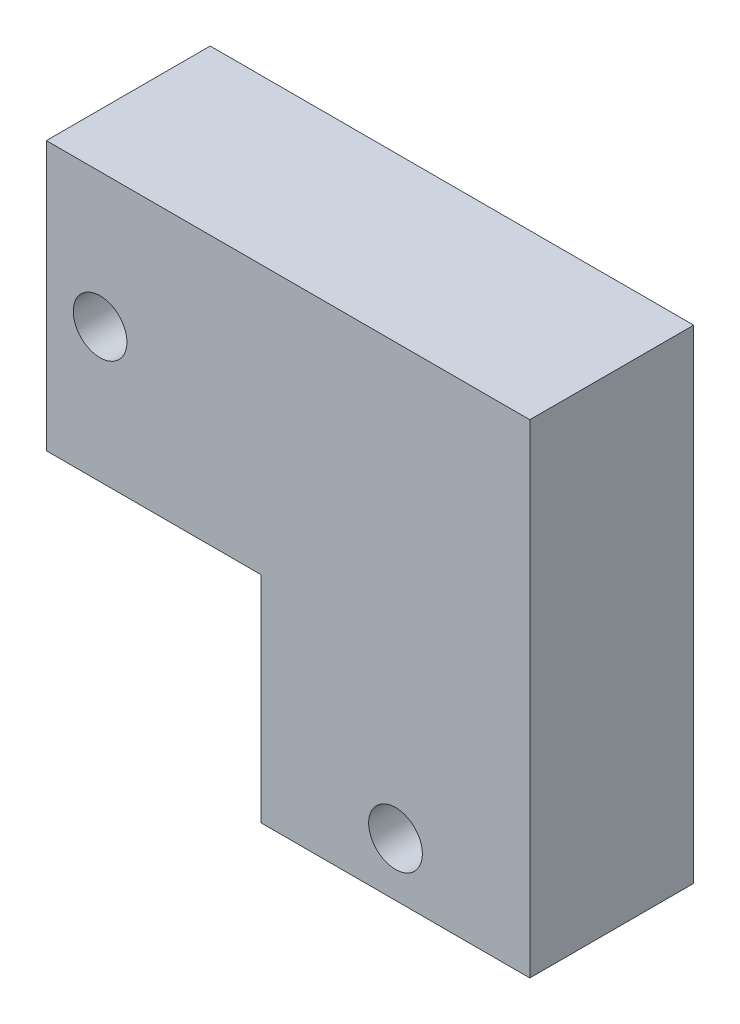
SolidWorks part; units mm, degrees
ref_plane "Front Plane" through (0, 0, 0) normal (0, 0, 1) x (1, 0, 0)
ref_plane "Top Plane" through (0, 0, 0) normal (0, 1, 0) x (1, 0, 0)
ref_plane "Right Plane" through (0, 0, 0) normal (1, 0, 0) x (0, 0, -1)
sketch "Sketch1" plane through (0, 0, 0) normal (0, 1, 0) x (1, 0, 0)
  line L1 (-12.5, -12.5) -> (12.5, -12.5)
  line L2 (-12.5, -12.5) -> (-12.5, 12.5)
  line L3 (-12.5, 12.5) -> (12.5, 12.5)
  line L4 (12.5, -12.5) -> (12.5, 12.5)
  line L5 (-12.5, -12.5) -> (12.5, 12.5) construction
  line L6 (-12.5, 12.5) -> (12.5, -12.5) construction
  point P0 (0, 0)
  dimension "D1" = 25
  dimension "D2" = 25
extrude "Boss-Extrude1" add sketch "Sketch1" along normal mid plane 45 contours L3 L4 L1 L2
sketch "Sketch3" plane through (0, -22.5, 0) normal (0, -1, 0) x (1, 0, 0)
  line L0 (0, 12.5) -> (0, 10.25) construction
  line L1 (-12.5, 12.5) -> (12.5, 12.5) construction
  line L2 (0, -12.5) -> (0, -9.9959) construction
  line L3 (-12.5, -12.5) -> (12.5, -12.5) construction
  line L4 (-12.5, 0) -> (-12.4984, 0) construction
  line L5 (-12.5, 12.5) -> (-12.5, -12.5) construction
  line L6 (12.5, 0) -> (12.4984, 0) construction
  line L7 (12.5, 12.5) -> (12.5, -12.5) construction
  line L8 (0, 10.25) -> (-2.75, 10.25)
  line L9 (-10.25, -10.25) -> (10.25, -10.25)
  line L10 (-10.25, -10.25) -> (-10.25, 10.25)
  line L11 (-10.25, 10.25) -> (10.25, 10.25)
  line L12 (10.25, -10.25) -> (10.25, 10.25)
  line L13 (-10.25, -10.25) -> (10.25, 10.25) construction
  line L14 (-10.25, 10.25) -> (10.25, -10.25) construction
  line L15 (-2.75, 10.25) -> (-2.75, 4.75)
  line L16 (-2.75, 4.75) -> (2.75, 4.75)
  line L17 (2.75, 4.75) -> (2.75, 10.25)
  line L18 (0, 10.25) -> (0, -9.9959) construction
  line L19 (-12.4984, 0) -> (12.4984, 0) construction
  line L20 (-2.75, -10.25) -> (-2.75, -4.75)
  line L21 (-2.75, -4.75) -> (2.75, -4.75)
  line L22 (2.75, -4.75) -> (2.75, -10.25)
  line L23 (-12.4984, 0) -> (-10.25, 2.75)
  line L24 (-10.25, 2.75) -> (-4.75, 2.75)
  line L25 (-4.75, 2.75) -> (-4.75, -2.75)
  line L26 (-4.75, -2.75) -> (-10.25, -2.75)
  line L27 (12.4984, 0) -> (10.25, 2.75)
  line L28 (10.25, 2.75) -> (4.75, 2.75)
  line L29 (4.75, 2.75) -> (4.75, -2.75)
  line L30 (4.75, -2.75) -> (10.25, -2.75)
  point P17 (0, 0)
  dimension "D1" = 5.5
  dimension "D2" = 5.5
  dimension "D3" = 5.5
  dimension "D4" = 5.5
  dimension "D5" = 2.75
  dimension "D6" = 5.5
  dimension "D7" = 2.75
  dimension "D8" = 5.5
  dimension "D9" = 2.75
  dimension "D10" = 5.5
  dimension "D11" = 2.25
  dimension "D12" = 2.25
  dimension "D13" = 5.5
sketch "Sketch4" plane through (-12.5, 0, 0) normal (-1, 0, 0) x (0, 0, 1)
  line L0 (0, 22.5) -> (0, 0) construction
  line L1 (12.5, 22.5) -> (-12.5, 22.5) construction
  line L3 (-12.5, 22.5) -> (-12.5, -22.5) construction
  line L6 (12.5, 22.5) -> (12.5, -22.5) construction
  line L8 (-12.5, 0) -> (12.5, 0) construction
  line L10 (-12.5, 22.5) -> (12.5, 22.5)
  line L11 (-12.5, 22.5) -> (-12.5, -2.5)
  line L12 (-12.5, -2.5) -> (12.5, -2.5)
  line L13 (12.5, 22.5) -> (12.5, -2.5)
  dimension "D1" = 25
extrude "Boss-Extrude2" add sketch "Sketch4" along normal blind 20
sketch "Sketch5" plane through (-32.5, 0, 0) normal (-1, 0, 0) x (0, 0, 1)
  line L0 (-12.5, 22.5) -> (12.5, -2.5) construction
  line L1 (0, 20.5) -> (0, -0.5) construction
  line L2 (-10.5, -0.5) -> (10.5, -0.5)
  line L3 (-10.5, -0.5) -> (-10.5, 20.5)
  line L4 (-10.5, 20.5) -> (10.5, 20.5)
  line L5 (10.5, -0.5) -> (10.5, 20.5)
  line L6 (-10.5, -0.5) -> (10.5, 20.5) construction
  line L7 (-10.5, 20.5) -> (10.5, -0.5) construction
  line L8 (-10.5, 10) -> (10.5, 10) construction
  line L9 (0, 20.5) -> (-2.75, 20.5)
  line L10 (-2.75, 20.5) -> (-2.75, 15)
  line L11 (-2.75, 15) -> (2.75, 15)
  line L12 (2.75, 15) -> (2.75, 20.5)
  line L13 (-10.5, 10) -> (-10.5, 7.25)
  line L14 (-10.5, 7.25) -> (-5, 7.25)
  line L15 (-5, 7.25) -> (-5, 12.75)
  line L16 (-5, 12.75) -> (-10.5, 12.75)
  line L17 (0, -0.5) -> (-2.75, -0.5)
  line L18 (-2.75, -0.5) -> (-2.75, 5)
  line L19 (-2.75, 5) -> (2.75, 5)
  line L20 (2.75, 5) -> (2.75, -0.5)
  line L21 (10.5, 7.25) -> (5, 7.25)
  line L22 (5, 7.25) -> (5, 12.75)
  line L23 (5, 12.75) -> (10.5, 12.75)
  point P4 (0, 10)
  dimension "D1" = 21
  dimension "D2" = 5.5
  dimension "D3" = 5.5
  dimension "D4" = 5.5
  dimension "D5" = 5.5
  dimension "D6" = 5.5
  dimension "D7" = 5.5
  dimension "D8" = 5.5
  dimension "D9" = 5.5
  dimension "D10" = 2.75
  dimension "D11" = 2.75
  dimension "D12" = 2.75
extrude "Cut-Extrude2" cut sketch "Sketch3" against normal blind 42.5 contours L30 L29 L28 L12 L11 L17 L16 L15 L10 L24 L25 L26 L9 L20 L21 L22
extrude "Cut-Extrude3" cut sketch "Sketch5" against normal blind 21 contours L22 L23 L5 L4 L12 L11 L10 L3 L16 L15 L14 L2 L18 L19 L20 L21
sketch "Sketch6" plane through (0, 0, -12.5) normal (0, 0, -1) x (-1, 0, 0)
  line L0 (0, -22.5) -> (0, -12.5) construction
  line L1 (12.5, -22.5) -> (-12.5, -22.5) construction
  line L2 (22.5, 10) -> (32.5, 10) construction
  line L3 (32.5, 22.5) -> (32.5, -2.5) construction
  circle A0 centre (0, -12.5) radius 2.25
  circle A1 centre (22.5, 10) radius 2.25
  dimension "D1" = 4.5
  dimension "D2" = 4.5
  dimension "D3" = 10
  dimension "D4" = 10
extrude "Cut-Extrude4" cut sketch "Sketch6" against normal blind 10
sketch "Sketch8" plane through (0, 22.5, 0) normal (0, 1, 0) x (1, 0, 0)
  line L0 (12.5, -12.5) -> (12.5, 12.5) construction
  line L1 (-32.5, 12.5) -> (12.5, 12.5)
  line L2 (-32.5, 12.5) -> (-32.5, 2.75)
  line L3 (-32.5, 2.75) -> (12.5, 2.75)
  line L4 (12.5, 12.5) -> (12.5, 2.75)
extrude "Cut-Extrude5" cut sketch "Sketch8" against normal blind 50
sketch "Sketch10" plane through (0, 0, 12.5) normal (0, 0, 1) x (1, 0, 0)
  line L0 (-32.5, 10) -> (12.5, 10) construction
  line L1 (-32.5, -2.5) -> (-32.5, 22.5) construction
  line L2 (12.5, 15) -> (12.5, -22.5) construction
  line L3 (0, -22.5) -> (0, 10) construction
  line L4 (-12.5, -22.5) -> (12.5, -22.5) construction
  circle A0 centre (-27.5, 10) radius 2.5
  circle A1 centre (0, -17.5) radius 2.5
  dimension "D1" = 5
  dimension "D2" = 5
  dimension "D3" = 5
  dimension "D4" = 5
extrude "Cut-Extrude7" cut sketch "Sketch10" against normal blind 10
sketch "Sketch11" plane through (0, 0, 4.75) normal (0, 0, -1) x (-1, 0, 0)
  line L1 (2.2226, -13.5502) -> (-2.3093, -13.6003)
  line L2 (-2.3093, -13.6003) -> (-4.5319, -17.55)
  line L3 (-4.5319, -17.55) -> (-2.2226, -21.4498)
  line L4 (-2.2226, -21.4498) -> (2.3093, -21.3997)
  line L5 (2.3093, -21.3997) -> (4.5319, -17.45)
  line L6 (4.5319, -17.45) -> (2.2226, -13.5502)
  line L7 (31.439, 12.2417) -> (27.5281, 14.5321)
  line L8 (27.5281, 14.5321) -> (23.5891, 12.2904)
  line L9 (23.5891, 12.2904) -> (23.561, 7.7583)
  line L10 (23.561, 7.7583) -> (27.4719, 5.4679)
  line L11 (27.4719, 5.4679) -> (31.4109, 7.7096)
  line L12 (31.4109, 7.7096) -> (31.439, 12.2417)
  circle A0 centre (0, -17.5) radius 3.925 construction
  circle A1 centre (27.5, 10) radius 3.925 construction
  dimension "D1" = 7.85
  dimension "D2" = 7.85
extrude "Cut-Extrude8" cut sketch "Sketch11" against normal blind 2.6
